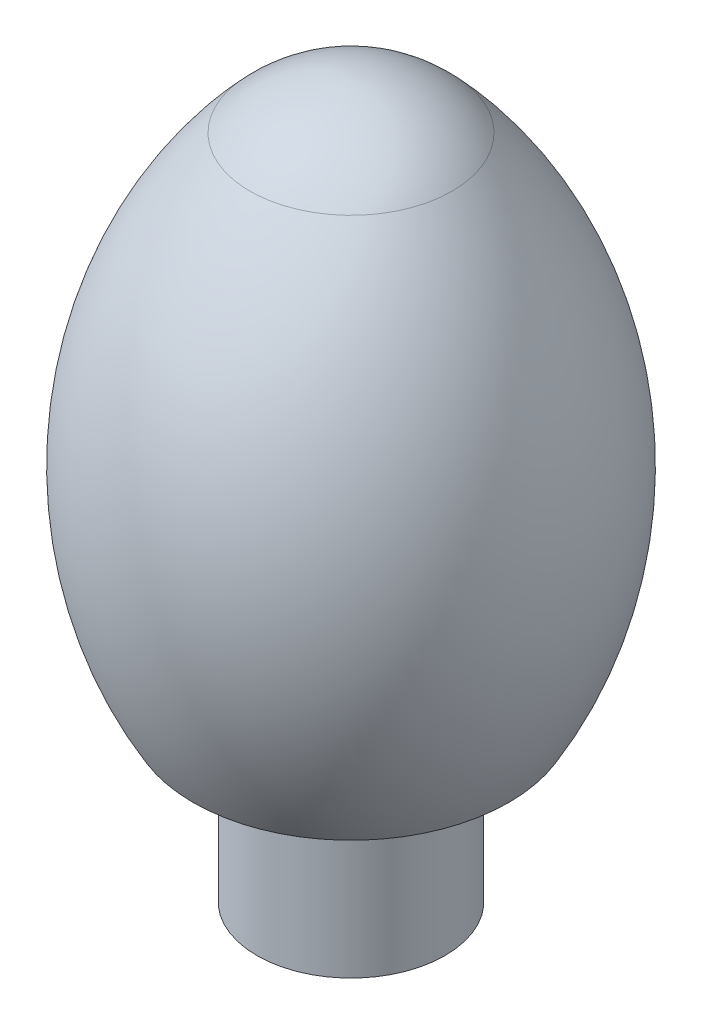
SolidWorks part; units mm, degrees
ref_plane "Front Plane" through (0, 0, 0) normal (0, 0, 1) x (1, 0, 0)
ref_plane "Top Plane" through (0, 0, 0) normal (0, 1, 0) x (1, 0, 0)
ref_plane "Right Plane" through (0, 0, 0) normal (1, 0, 0) x (0, 0, -1)
sketch "Sketch1" plane through (0, 0, 0) normal (0, 1, 0) x (1, 0, 0)
  circle A0 centre (0, 0) radius 5.08
  dimension "D1" = 10.16
extrude "Boss-Extrude1" add sketch "Sketch1" along normal blind 10.16
sketch "Sketch2" plane through (0, 0, 0) normal (0, 0, 1) x (1, 0, 0)
  line L0 (0, 8.89) -> (0, 38.4451)
  line L1 (0, 8.89) -> (8.5299, 8.89)
  line L3 (5.08, 10.16) -> (-5.08, 10.16) construction
  arc A0 (8.5299, 8.89) -> (5.4657, 35.9671) centre (-11.1805, 20.3714) ccw
  arc A1 (5.4657, 35.9671) -> (0, 38.4451) centre (-0.2617, 30.6011) ccw
  point P0 (8.5326, 8.89)
  point P1 (8.5326, 31.8481)
  dimension "D3" = 1.27
revolve "Revolve1" add sketch "Sketch2" angle 360 about L0
